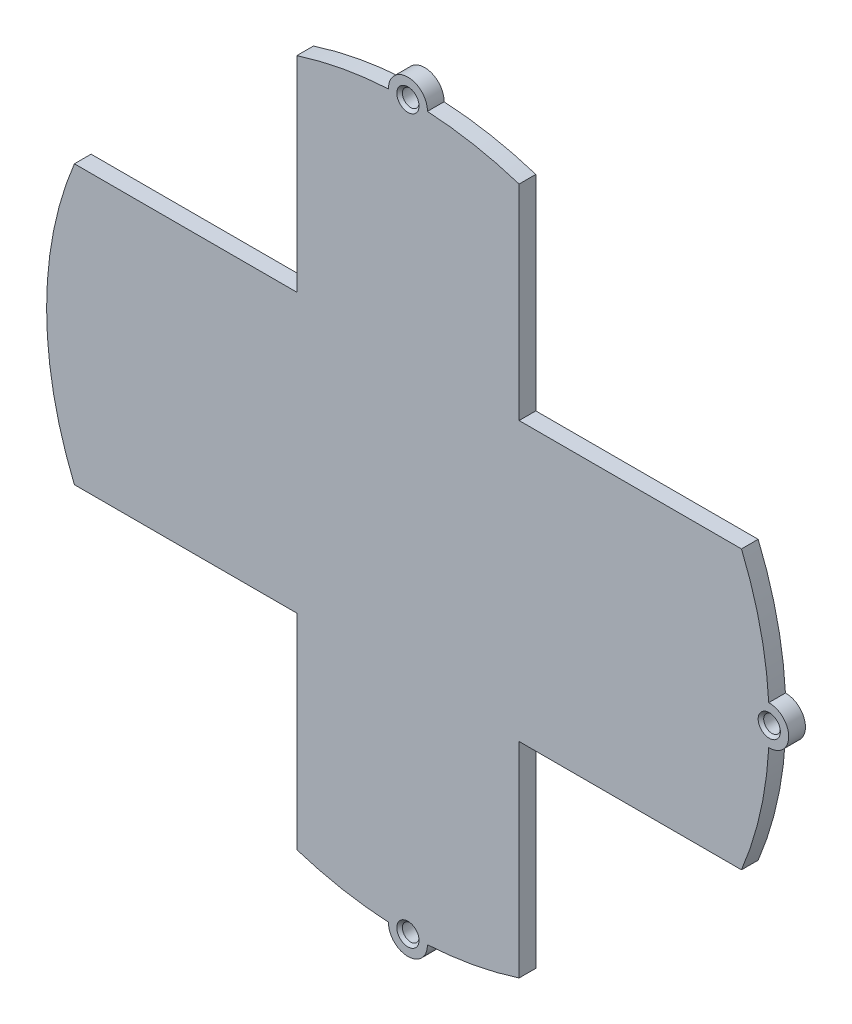
SolidWorks part; units mm, degrees
ref_plane "前视基准面" through (0, 0, 0) normal (0, 0, 1) x (1, 0, 0)
ref_plane "上视基准面" through (0, 0, 0) normal (0, 1, 0) x (1, 0, 0)
ref_plane "右视基准面" through (0, 0, 0) normal (1, 0, 0) x (0, 0, -1)
sketch "草图1" plane through (0, 0, 0) normal (0, 0, 1) x (1, 0, 0)
  line L0 (20, -25) -> (20, -61.8466)
  line L1 (-60, 25) -> (-20, 25)
  line L3 (-60, -25) -> (-20, -25)
  line L6 (-20, 61.8466) -> (-20, 25)
  line L8 (20, 61.8466) -> (20, 25)
  line L9 (-20, -25) -> (-20, -61.8466)
  line L10 (20, 25) -> (60, 25)
  line L11 (20, -25) -> (60, -25)
  arc A1 (-60, 25) -> (-60, -25) centre (0, 0) ccw
  arc A2 (20, 61.8466) -> (-20, 61.8466) centre (0, 0) ccw
  arc A3 (60, -25) -> (60, 25) centre (0, 0) ccw
  arc A4 (-20, -61.8466) -> (20, -61.8466) centre (0, 0) ccw
  dimension "D1" = 130
  dimension "D2" = 40
  dimension "D3" = 50
  dimension "D4" = 25
  dimension "D5" = 20
extrude "凸台-拉伸1" add sketch "草图1" along normal blind 3
sketch "草图2" plane through (0, 0, 3) normal (0, 0, 1) x (1, 0, 0)
  circle A0 centre (65, 0) radius 3.5
  arc A1 (60, -25) -> (60, 25) centre (0, 0) ccw construction
  circle A2 centre (0, 65) radius 3.5
  arc A3 (20, 61.8466) -> (-20, 61.8466) centre (0, 0) ccw construction
  circle A4 centre (0, -65) radius 3.5
  arc A5 (-20, -61.8466) -> (20, -61.8466) centre (0, 0) ccw construction
  dimension "D1" = 7
  dimension "D2" = 7
  dimension "D3" = 7
extrude "凸台-拉伸2" add sketch "草图2" against normal blind 3
sketch "草图3" plane through (0, 0, 3) normal (0, 0, 1) x (1, 0, 0)
  circle A0 centre (0, 65) radius 1.5
  circle A1 centre (65, 0) radius 1.5
  circle A2 centre (0, -65) radius 1.5
  dimension "D1" = 3
  dimension "D2" = 3
  dimension "D3" = 3
extrude "切除-拉伸1" cut sketch "草图3" against normal blind 3
chamfer "倒角1" distance 0.5 angle 45 3 edges at (1.5, 65, 3) (66.5, 0, 3) (1.5, -65, 3)
